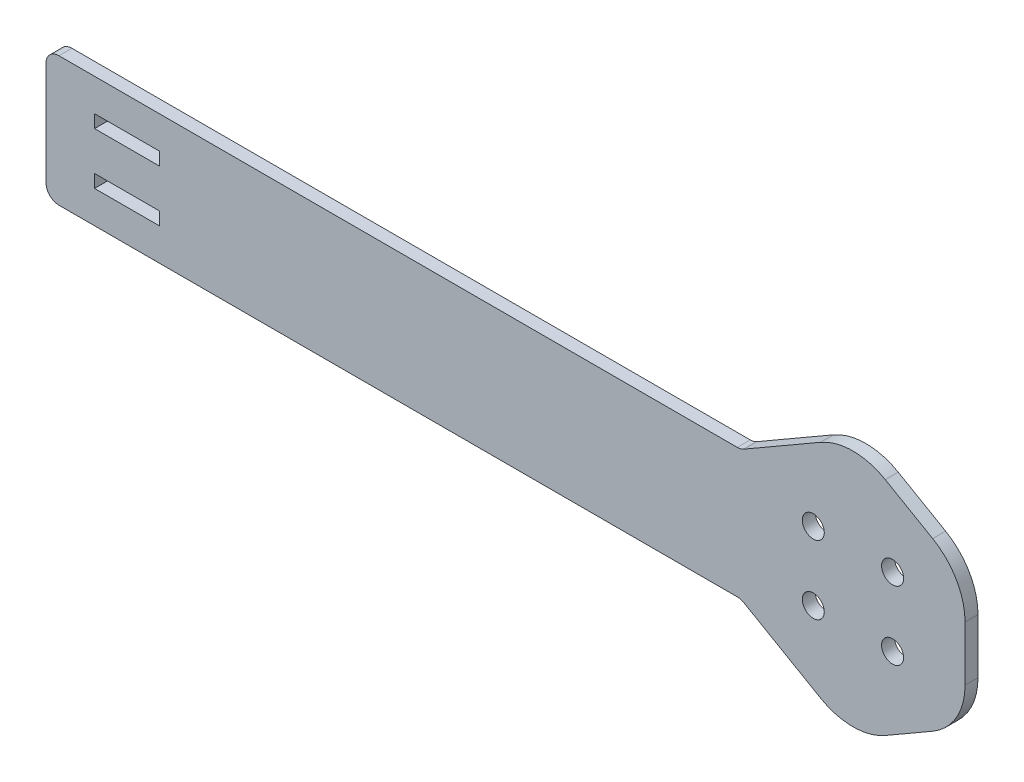
SolidWorks part; units mm, degrees
material "Thornel Mat VMA"
ref_plane "Ön Düzlem" through (0, 0, 0) normal (0, 0, 1) x (1, 0, 0)
ref_plane "Üst Düzlem" through (0, 0, 0) normal (0, 1, 0) x (1, 0, 0)
ref_plane "Sağ Düzlem" through (0, 0, 0) normal (1, 0, 0) x (0, 0, -1)
sketch "Sketch1" plane through (0, 0, 0) normal (0, 0, 1) x (1, 0, 0)
  line L0 (115.9912, -5) -> (0, -5) construction
  line L1 (0, 0) -> (140, 0)
  line L2 (0, 0) -> (0, -40)
  line L3 (0, -40) -> (140, -40)
  line L4 (140, 0) -> (140, -40)
  line L5 (141.972, -10) -> (124.6515, 0)
  line L6 (124.6515, 0) -> (107.331, -10)
  line L7 (107.331, -10) -> (107.331, -30)
  line L8 (107.331, -30) -> (124.6515, -40)
  line L9 (124.6515, -40) -> (141.972, -30)
  line L10 (141.972, -30) -> (141.972, -10)
  line L11 (115.9912, -35) -> (0, -35) construction
  line L12 (124.6515, -20) -> (112.4015, -20) construction
  line L13 (112.4015, -20) -> (118.5265, -20) construction
  line L14 (118.5265, -20) -> (118.5265, -30.6088) construction
  line L15 (118.5265, -20) -> (118.5265, -9.3912) construction
  line L16 (124.6515, -20) -> (136.9015, -20) construction
  line L17 (130.7765, -20) -> (130.7765, -9.3912) construction
  line L18 (130.7765, -20) -> (130.7765, -30.6088) construction
  line L19 (107.331, -10) -> (0, -10)
  line L20 (7.5, -15) -> (22.5, -15) construction
  line L21 (7.5, -15) -> (7.5, -25) construction
  line L22 (7.5, -25) -> (22.5, -25) construction
  line L23 (22.5, -15) -> (22.5, -25) construction
  line L24 (7.5, -15) -> (22.5, -25) construction
  line L25 (7.5, -25) -> (22.5, -15) construction
  line L27 (7.5, -15) -> (17.5, -15)
  line L28 (7.5, -15) -> (7.5, -17)
  line L29 (7.5, -17) -> (17.5, -17)
  line L30 (17.5, -15) -> (17.5, -17)
  line L31 (7.5, -25) -> (17.5, -25)
  line L32 (7.5, -25) -> (7.5, -23)
  line L33 (7.5, -23) -> (17.5, -23)
  line L34 (17.5, -25) -> (17.5, -23)
  line L42 (107.331, -30) -> (0, -30)
  circle A0 centre (124.6515, -20) radius 17.3205 construction
  circle A1 centre (124.6515, -20) radius 12.25
  circle A2 centre (118.5265, -14.6956) radius 1.7
  circle A3 centre (130.7765, -14.6956) radius 1.7
  circle A4 centre (130.7765, -25.3044) radius 1.7
  circle A5 centre (118.5265, -25.3044) radius 1.7
  point P34 (15, -20)
  dimension "D6" = 24.5
  dimension "D7" = 3.4
  dimension "D8" = 15
  dimension "D1" = 140
  dimension "D2" = 40
  dimension "D3" = 0
  dimension "D4" = 0
  dimension "D5" = 360
  dimension "D9" = 10
  dimension "D10" = 10
  dimension "D11" = 7.5
  dimension "D12" = 2
  dimension "D13" = 10
  dimension "D14" = 10
  dimension "D15" = 2
extrude "Boss-Extrude3" add sketch "Sketch1" along normal blind 2 contours L42 L7 L19 L2 L34 L31 L32 L33 L27 L30 L29 L28 | L8 L9 L4 L5 L6 L7 A1 | A1 A5 A4 A3 A2 | L9 L10 L5 L4
fillet "Fillet5" radius 10 1 edges at (124.6515, 0, 1)
fillet "Fillet6" radius 10 1 edges at (141.972, -10, 1)
fillet "Fillet7" radius 10 1 edges at (141.972, -30, 1)
fillet "Fillet8" radius 10 1 edges at (124.6515, -40, 1)
fillet "Fillet14" radius 2 2 edges at (0, -30, 1) (0, -10, 1)
fillet "Fillet15" radius 2 1 edges at (107.331, -10, 1)
fillet "Fillet16" radius 2 1 edges at (107.331, -30, 1)
ref_plane "Plane1" through (7.5, -15, 2) normal (0, -1, 0) x (-1, 0, 0)
sketch "Sketch4" plane through (0, 0, 2) normal (0, 0, 1) x (1, 0, 0)
  line L0 (17.5, -15) -> (17.5, -17) construction
  line L1 (17.5, -14.5) -> (7.5, -14.5)
  line L2 (17.5, -14.5) -> (17.5, -17.5)
  line L3 (17.5, -17.5) -> (7.5, -17.5)
  line L4 (7.5, -14.5) -> (7.5, -17.5)
  line L5 (7.5, -15) -> (7.5, -17) construction
  line L6 (7.5, -15) -> (17.5, -15) construction
  line L7 (7.5, -25) -> (7.5, -23) construction
  line L8 (7.5, -22.5) -> (17.5, -22.5)
  line L9 (7.5, -22.5) -> (7.5, -25.5)
  line L10 (7.5, -25.5) -> (17.5, -25.5)
  line L11 (17.5, -22.5) -> (17.5, -25.5)
  line L12 (17.5, -25) -> (17.5, -23) construction
  line L13 (7.5, -23) -> (17.5, -23) construction
  dimension "D1" = 3
  dimension "D2" = 0.5
  dimension "D3" = 3
  dimension "D4" = 0.5
